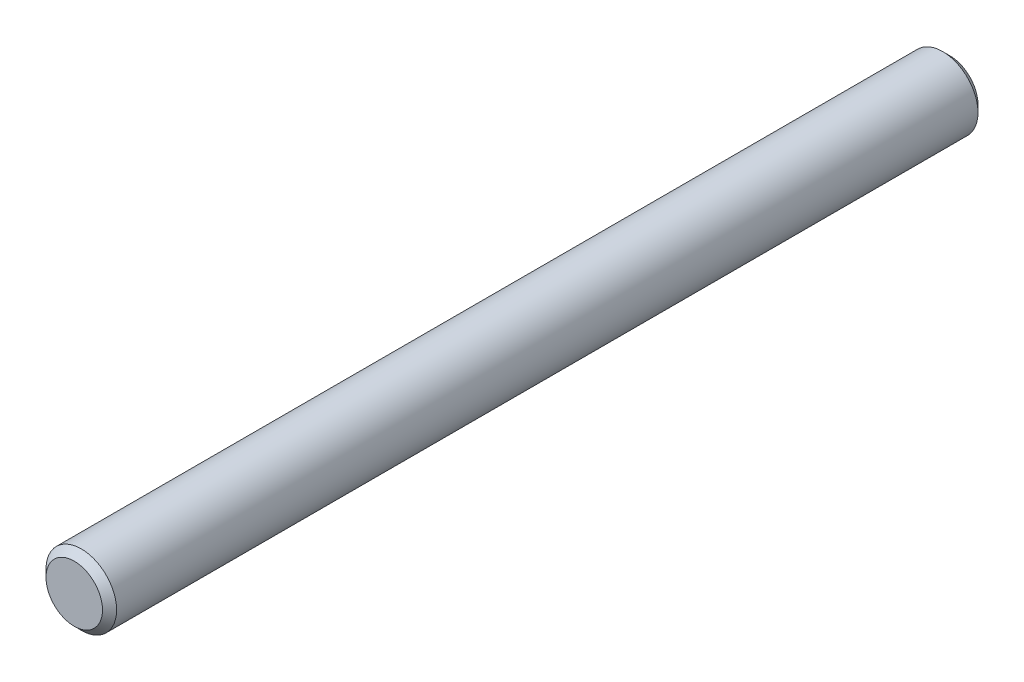
SolidWorks part; units mm, degrees
material "201 Stal nierdzewna odprężona (SS)"
ref_plane "Płaszczyzna przednia" through (0, 0, 0) normal (0, 0, 1) x (1, 0, 0)
ref_plane "Płaszczyzna górna" through (0, 0, 0) normal (0, 1, 0) x (1, 0, 0)
ref_plane "Płaszczyzna prawa" through (0, 0, 0) normal (1, 0, 0) x (0, 0, -1)
sketch "Szkic1" plane through (0, 0, 0) normal (0, 0, 1) x (1, 0, 0)
  circle A0 centre (0, 0) radius 2.5
  dimension "D1" = 5
extrude "Dodanie-wyciągnięcie1" add sketch "Szkic1" along normal blind 62
chamfer "Sfazowanie1" distance 0.5 angle 45 2 edges at (2.5, 0, 0) (2.5, 0, 62)
